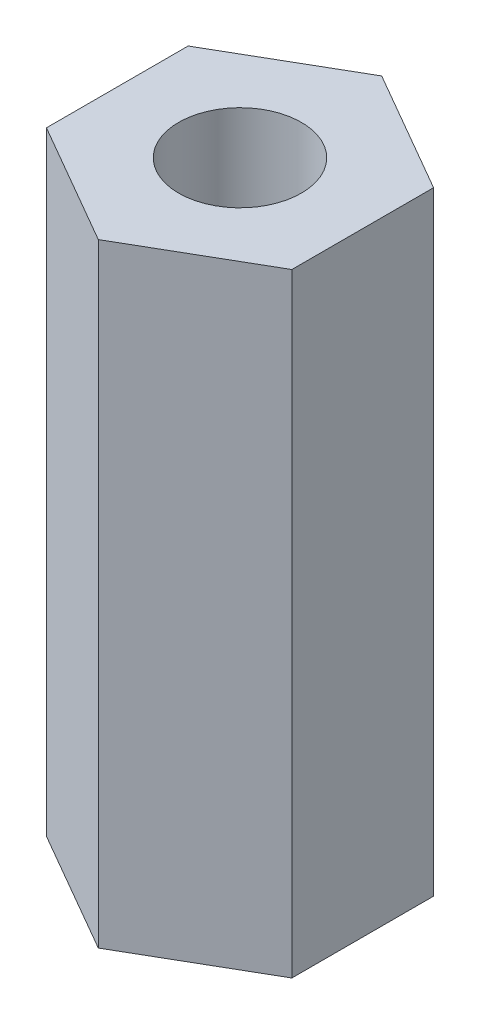
SolidWorks part; units mm, degrees
ref_plane "Front Plane" through (0, 0, 0) normal (0, 0, 1) x (1, 0, 0)
ref_plane "Top Plane" through (0, 0, 0) normal (0, 1, 0) x (1, 0, 0)
ref_plane "Right Plane" through (0, 0, 0) normal (1, 0, 0) x (0, 0, -1)
sketch "Sketch1" plane through (0, 0, 0) normal (0, 1, 0) x (1, 0, 0)
  line L1 (0, 3.4641) -> (-3, 1.7321)
  line L2 (-3, 1.7321) -> (-3, -1.7321)
  line L3 (-3, -1.7321) -> (0, -3.4641)
  line L4 (0, -3.4641) -> (3, -1.7321)
  line L5 (3, -1.7321) -> (3, 1.7321)
  line L6 (3, 1.7321) -> (0, 3.4641)
  circle A0 centre (0, 0) radius 3 construction
  circle A1 centre (0, 0) radius 1.5
  dimension "D1" = 6
extrude "Boss-Extrude1" add sketch "Sketch1" along normal blind 15
